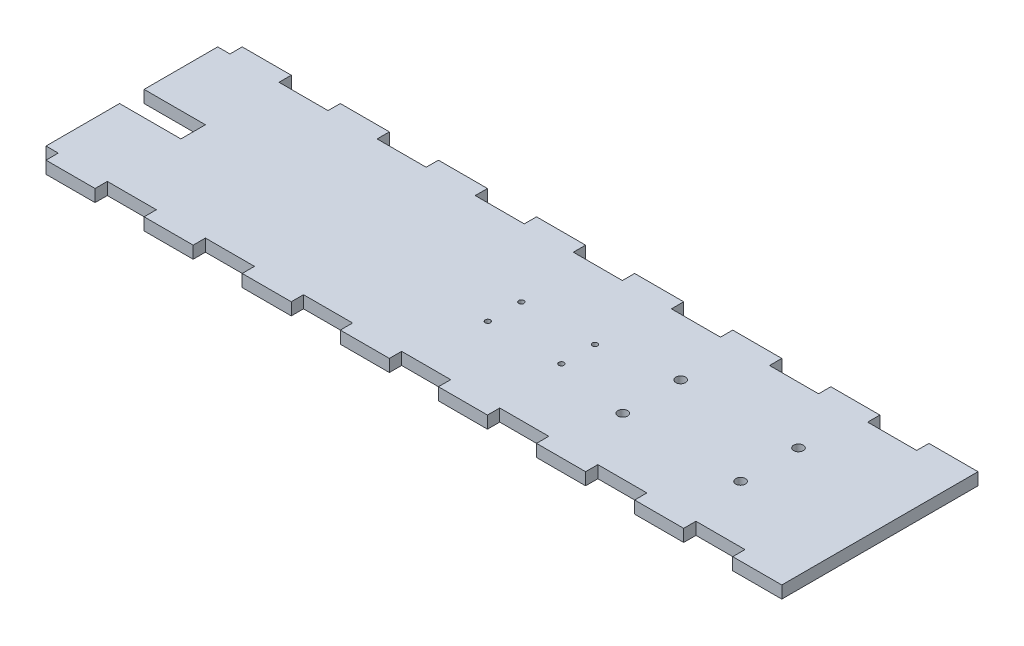
SolidWorks part; units mm, degrees
material "Acrylic (Medium-high impact)"
ref_plane "Front Plane" through (0, 0, 0) normal (0, 0, 1) x (1, 0, 0)
ref_plane "Top Plane" through (0, 0, 0) normal (0, 1, 0) x (1, 0, 0)
ref_plane "Right Plane" through (0, 0, 0) normal (1, 0, 0) x (0, 0, -1)
sketch "Sketch1" plane through (0, 0, 0) normal (0, 1, 0) x (1, 0, 0)
  line L0 (95.25, 0) -> (95.25, -50.8) construction
  line L5 (0, 0) -> (190.5, 0)
  line L6 (0, 0) -> (0, -50.8)
  line L7 (0, -50.8) -> (190.5, -50.8)
  line L8 (190.5, 0) -> (190.5, -50.8)
  line L9 (190.5, -25.4) -> (0, -25.4) construction
  line L14 (12.7, 0) -> (12.7, -3.175)
  line L15 (12.7, -50.8) -> (25.4, -50.8)
  line L16 (12.7, -50.8) -> (12.7, -47.625)
  line L17 (12.7, -47.625) -> (25.4, -47.625)
  line L18 (25.4, -50.8) -> (25.4, -47.625)
  line L19 (12.7, -3.175) -> (25.4, -3.175)
  line L20 (25.4, 0) -> (25.4, -3.175)
  line L21 (38.1, 0) -> (38.1, -3.175)
  line L22 (38.1, -3.175) -> (50.8, -3.175)
  line L23 (50.8, 0) -> (50.8, -3.175)
  line L24 (50.8, -50.8) -> (50.8, -47.625)
  line L25 (38.1, -47.625) -> (50.8, -47.625)
  line L26 (38.1, -50.8) -> (38.1, -47.625)
  line L27 (63.5, 0) -> (63.5, -3.175)
  line L28 (63.5, -3.175) -> (76.2, -3.175)
  line L29 (76.2, 0) -> (76.2, -3.175)
  line L30 (76.2, -50.8) -> (76.2, -47.625)
  line L31 (63.5, -47.625) -> (76.2, -47.625)
  line L32 (63.5, -50.8) -> (63.5, -47.625)
  line L33 (88.9, 0) -> (88.9, -3.175)
  line L34 (88.9, -3.175) -> (101.6, -3.175)
  line L35 (101.6, 0) -> (101.6, -3.175)
  line L36 (101.6, -50.8) -> (101.6, -47.625)
  line L37 (88.9, -47.625) -> (101.6, -47.625)
  line L38 (88.9, -50.8) -> (88.9, -47.625)
  line L39 (114.3, 0) -> (114.3, -3.175)
  line L40 (114.3, -3.175) -> (127, -3.175)
  line L41 (127, 0) -> (127, -3.175)
  line L42 (127, -50.8) -> (127, -47.625)
  line L43 (114.3, -47.625) -> (127, -47.625)
  line L44 (114.3, -50.8) -> (114.3, -47.625)
  line L45 (139.7, 0) -> (139.7, -3.175)
  line L46 (139.7, -3.175) -> (152.4, -3.175)
  line L47 (152.4, 0) -> (152.4, -3.175)
  line L48 (152.4, -50.8) -> (152.4, -47.625)
  line L49 (139.7, -47.625) -> (152.4, -47.625)
  line L50 (139.7, -50.8) -> (139.7, -47.625)
  line L51 (165.1, 0) -> (165.1, -3.175)
  line L52 (165.1, -3.175) -> (177.8, -3.175)
  line L53 (177.8, 0) -> (177.8, -3.175)
  line L54 (177.8, -50.8) -> (177.8, -47.625)
  line L55 (165.1, -47.625) -> (177.8, -47.625)
  line L56 (165.1, -50.8) -> (165.1, -47.625)
  dimension "D1" = 50.8
  dimension "D2" = 190.5
  dimension "D3" = 3.175
  dimension "D4" = 12.7
  dimension "D5" = 12.7
  dimension "D7" = 12.7
  dimension "D6" = 7
extrude "Boss-Extrude1" add sketch "Sketch1" along normal blind 3.175 contours L7 L56 L55 L54 L8 L5 L53 L52 L51 L47 L46 L45 L41 L40 L39 L35 L34 L33 L29 L28 L27 L23 L22 L21 L20 L19 L14 L6 L16 L17 L18 L26 L25 L24 L32 L31 L30 L38 L37
sketch "Sketch2" plane through (0, 3.175, 0) normal (0, 1, 0) x (1, 0, 0)
  line L2 (0, 0) -> (0, -50.8) construction
  line L3 (0, -28.575) -> (12.7, -28.575)
  line L4 (0, -28.575) -> (0, -22.225)
  line L5 (0, -22.225) -> (12.7, -22.225)
  line L6 (12.7, -28.575) -> (12.7, -22.225)
  point P12 (0, -25.4)
  point P13 (0, -25.4)
  dimension "D3" = 6.35
  dimension "D4" = 12.7
extrude "Cut-Extrude1" cut sketch "Sketch2" against normal through all
sketch "Sketch3" plane through (0, 0, 0) normal (-1, 0, 0) x (0, 0, 1)
  line L1 (3.175, 0) -> (22.225, 0)
  line L2 (3.175, 0) -> (3.175, 3.175)
  line L3 (3.175, 3.175) -> (22.225, 3.175)
  line L4 (22.225, 0) -> (22.225, 3.175)
  line L5 (47.625, 0) -> (28.575, 0)
  line L6 (47.625, 0) -> (47.625, 3.175)
  line L7 (47.625, 3.175) -> (28.575, 3.175)
  line L8 (28.575, 0) -> (28.575, 3.175)
  line L9 (50.8, 3.175) -> (50.8, 0) construction
  line L10 (0, 3.175) -> (0, 0) construction
  line L11 (0, 0) -> (22.225, 0) construction
  dimension "D1" = 3.175
  dimension "D2" = 3.175
extrude "Boss-Extrude2" add sketch "Sketch3" along normal blind 6.35
sketch "Sketch5" plane through (0, 3.175, 0) normal (0, 1, 0) x (1, 0, 0)
  line L0 (190.5, 0) -> (190.5, -50.8) construction
  line L1 (161.925, -17.9) -> (131.425, -17.9) construction
  line L2 (161.925, -17.9) -> (161.925, -32.9) construction
  line L3 (161.925, -32.9) -> (131.425, -32.9) construction
  line L4 (131.425, -17.9) -> (131.425, -32.9) construction
  line L5 (112.375, -29.7434) -> (112.375, -21.0566) construction
  circle A0 centre (161.925, -17.9) radius 1.25
  circle A1 centre (161.925, -32.9) radius 1.25
  circle A2 centre (131.425, -32.9) radius 1.25
  circle A3 centre (131.425, -17.9) radius 1.25
  circle A4 centre (112.375, -21.0566) radius 0.6731
  circle A5 centre (112.375, -29.7434) radius 0.6731
  circle A6 centre (93.325, -21.0566) radius 0.6731
  circle A7 centre (93.325, -29.7434) radius 0.6731
  point P4 (161.925, -25.4)
  point P5 (190.5, -25.4)
  point P18 (112.375, -25.4)
  dimension "D4" = 2.5
  dimension "D5" = 1.3462
  dimension "D1" = 15
  dimension "D2" = 30.5
  dimension "D3" = 28.575
  dimension "D6" = 8.6868
  dimension "D7" = 19.05
  dimension "D8" = 19.05
extrude "Cut-Extrude3" cut sketch "Sketch5" against normal through all contours A3 | A2 | A4 | A5 | A7 | A6 | A1 | A0
sketch "Sketch6" plane through (0, 3.175, 0) normal (0, 1, 0) x (1, 0, 0)
  line L0 (-6.35, -47.625) -> (0, -47.625) construction
  line L1 (-6.35, -3.175) -> (-3.175, -3.175)
  line L2 (-6.35, -3.175) -> (-6.35, -47.625)
  line L3 (-6.35, -47.625) -> (-3.175, -47.625)
  line L4 (-3.175, -3.175) -> (-3.175, -47.625)
  dimension "D1" = 3.175
extrude "Cut-Extrude4" cut sketch "Sketch6" against normal through all
